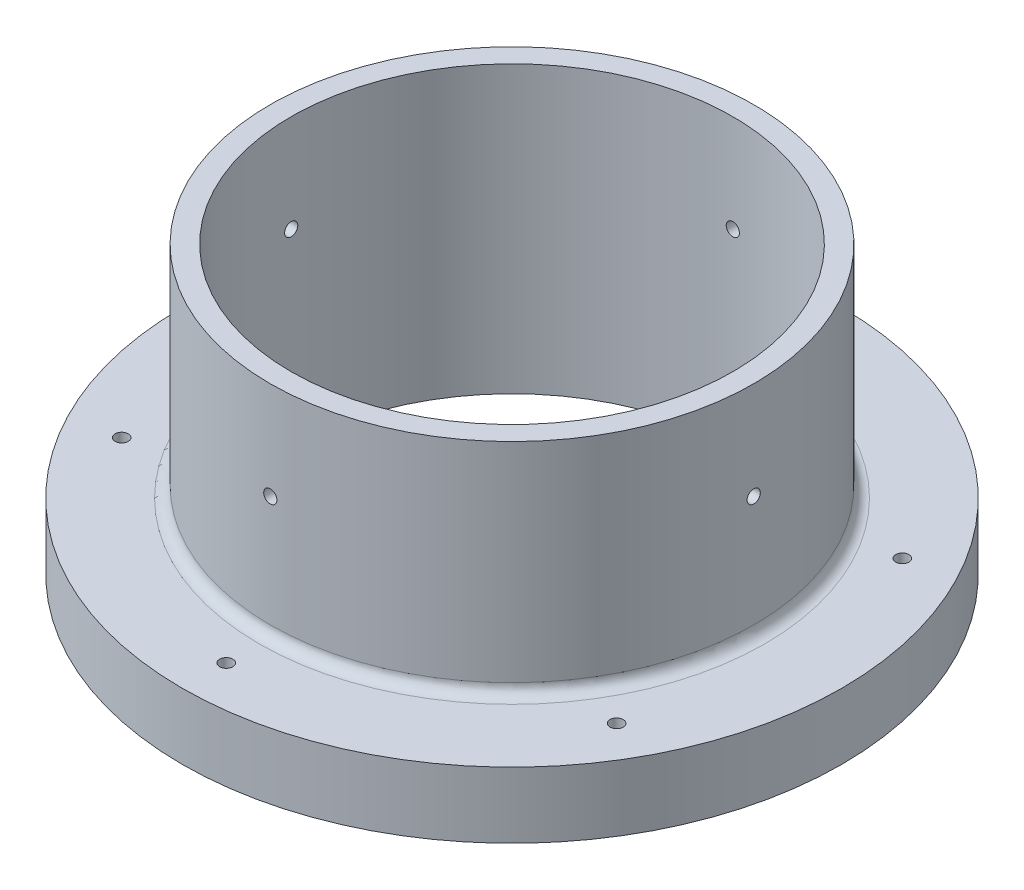
SolidWorks part; units mm, degrees
ref_plane "Front Plane" through (0, 0, 0) normal (0, 0, 1) x (1, 0, 0)
ref_plane "Top Plane" through (0, 0, 0) normal (0, 1, 0) x (1, 0, 0)
ref_plane "Right Plane" through (0, 0, 0) normal (1, 0, 0) x (0, 0, -1)
sketch "Sketch5" plane through (0, 0, 0) normal (0, 1, 0) x (1, 0, 0)
  circle A0 centre (0, 0) radius 50.25
  circle A1 centre (0, 0) radius 55
  dimension "D1" = 100.5
  dimension "D2" = 110
  dimension "D3" = 4.75
extrude "Boss-Extrude1" add sketch "Sketch5" along normal blind 50
sketch "Sketch7" plane through (0, 0, 0) normal (0, 1, 0) x (1, 0, 0)
  circle A0 centre (0, 0) radius 69.5
  dimension "D1" = 139
extrude "Boss-Extrude2" [suppressed] add sketch "Sketch7" along normal blind 5
sketch "Sketch8" plane through (0, 0, 0) normal (1, 0, 0) x (0, 0, -1)
  line L0 (0, 27.5) -> (0, -27.5) construction
  line L1 (55, 50) -> (-55, 50) construction
  circle A0 centre (0, 27.82) radius 1.5
  dimension "D1" = 3
  dimension "D2" = 22.18
extrude "Cut-Extrude1" cut sketch "Sketch8" against normal blind 106 and the other way blind 211 contours A0
sketch "Sketch9" plane through (0, 0, 0) normal (0, 0, 1) x (1, 0, 0)
  line L0 (55, 50) -> (-55, 50) construction
  circle A0 centre (0, 27.82) radius 1.5
  dimension "D1" = 3
  dimension "D2" = 22.18
extrude "Cut-Extrude2" cut sketch "Sketch9" against normal through all both and the other way through all contours A0
ref_plane "Plane1" through (0, -15, 0) normal (0, 1, 0) x (1, 0, 0)
sketch "Sketch14" plane through (0, -15, 0) normal (0, 1, 0) x (1, 0, 0)
  circle A0 centre (0, 0) radius 75
  circle A4 centre (0, 0) radius 50.25
  dimension "D1" = 150
  dimension "D2" = 100.5
extrude "Boss-Extrude4" add sketch "Sketch14" along normal up to surface (15 mm away) contours A0
fillet "Fillet3" radius 2.5 1 edges at (0, 0, 55)
sketch "Sketch15" plane through (0, -15, 0) normal (0, -1, 0) x (1, 0, 0)
  circle A2 centre (0, 65) radius 1.5
  dimension "D1" = 65
extrude "Cut-Extrude3" cut sketch "Sketch15" against normal through all contours A2
pattern_circular "CirPattern1" count 6 over 360 about axis through (0, 0, 0) along (0, 1, 0) of "Cut-Extrude3"
